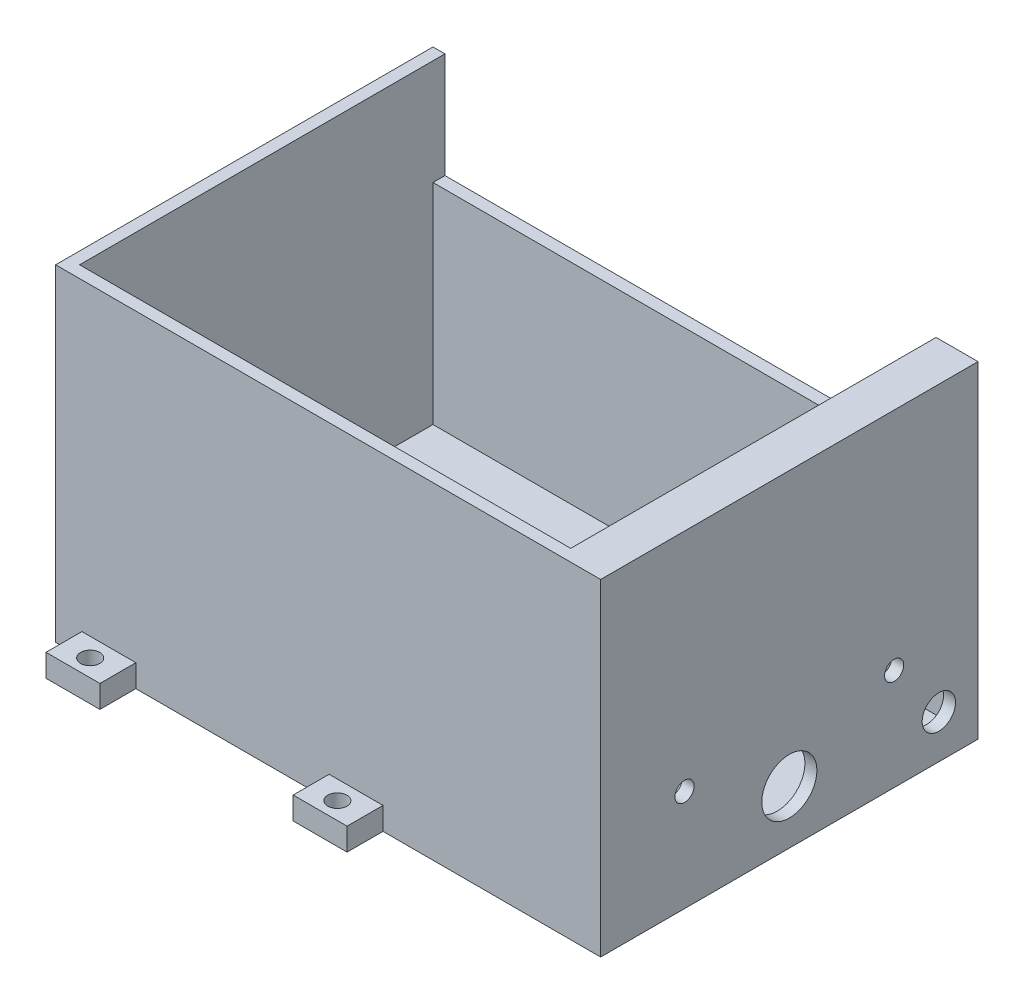
SolidWorks part; units mm, degrees
ref_plane "前视基准面" through (0, 0, 0) normal (0, 0, 1) x (1, 0, 0)
ref_plane "上视基准面" through (0, 0, 0) normal (0, 1, 0) x (1, 0, 0)
ref_plane "右视基准面" through (0, 0, 0) normal (1, 0, 0) x (0, 0, -1)
sketch "草图1" plane through (0, 0, 0) normal (0, 1, 0) x (1, 0, 0)
  line L1 (-43, 31.5) -> (43, 31.5)
  line L2 (-43, 31.5) -> (-43, -31.5)
  line L3 (-43, -31.5) -> (43, -31.5)
  line L4 (43, 31.5) -> (43, -31.5)
  point P4 (0, 31.5)
  point P7 (43, 0)
  dimension "D1" = 86
  dimension "D2" = 63
extrude "凸台-拉伸1" add sketch "草图1" along normal blind 2
sketch "草图2" plane through (0, 2, 0) normal (0, 1, 0) x (1, 0, 0)
  line L4 (-43, 31.5) -> (-43, -31.5)
  line L5 (-43, -31.5) -> (43, -31.5)
  line L6 (43, -31.5) -> (43, 31.5)
  line L7 (43, 31.5) -> (-43, 31.5)
  line L8 (-43, 31.5) -> (-43, -31.5)
  line L9 (-43, -31.5) -> (43, -31.5)
  line L10 (43, -31.5) -> (43, 31.5)
  line L11 (43, 31.5) -> (-43, 31.5)
  line L16 (-41, 29.5) -> (-41, -29.5)
  line L17 (-41, -29.5) -> (41, -29.5)
  line L18 (41, -29.5) -> (41, 29.5)
  line L19 (41, 29.5) -> (-41, 29.5)
  line L20 (-41, 29.5) -> (-41, -29.5)
  line L21 (-41, -29.5) -> (41, -29.5)
  line L22 (41, -29.5) -> (41, 29.5)
  line L23 (41, 29.5) -> (-41, 29.5)
  dimension "D1" = 0
  dimension "D2" = 2
extrude "凸台-拉伸3" add sketch "草图2" along normal blind 52.6
sketch "草图4" plane through (0, 0, -29.5) normal (0, 0, 1) x (1, 0, 0)
  line L0 (-41, 37) -> (41, 37)
  line L1 (-41, 54.6) -> (-41, 37)
  line L4 (-41, 2) -> (41, 2)
  line L5 (41, 2) -> (41, 54.6)
  line L6 (41, 54.6) -> (-41, 54.6)
  line L7 (-41, 54.6) -> (-41, 2)
  line L8 (-41, 2) -> (41, 2)
  line L9 (41, 2) -> (41, 54.6)
  line L10 (41, 54.6) -> (-41, 54.6)
  line L11 (-41, 54.6) -> (-41, 2)
  line M7 (41, 2) -> (41, 54.6)
  line M8 (41, 54.6) -> (-41, 54.6)
  line M9 (-41, 54.6) -> (-41, 2)
  dimension "D2" = 17.6
  dimension "D1" = 0
extrude "切除-拉伸1" cut sketch "草图4" against normal blind 52.6 contours L0 M9 M7 M8
sketch "草图5" plane through (43, 0, 0) normal (1, 0, 0) x (0, 0, -1)
  line L0 (0, 8.9545) -> (0, 16.9545)
  line L4 (-31.5, 0) -> (31.5, 0)
  line L5 (31.5, 0) -> (31.5, 54.6)
  line L6 (31.5, 54.6) -> (-31.5, 54.6)
  line L7 (-31.5, 54.6) -> (-31.5, 0)
  line L8 (-31.5, 0) -> (31.5, 0)
  line L9 (31.5, 0) -> (31.5, 54.6)
  line L10 (31.5, 54.6) -> (-31.5, 54.6)
  line L11 (-31.5, 54.6) -> (-31.5, 0)
  line L12 (-17.5, 16.9545) -> (17.5, 16.9545) construction
  line L16 (-29.5, 2) -> (29.5, 2)
  line L17 (29.5, 2) -> (29.5, 52.6)
  line L18 (29.5, 52.6) -> (-29.5, 52.6)
  line L19 (-29.5, 52.6) -> (-29.5, 2)
  line L20 (-29.5, 2) -> (29.5, 2)
  line L21 (29.5, 2) -> (29.5, 52.6)
  line L22 (29.5, 52.6) -> (-29.5, 52.6)
  line L23 (-29.5, 52.6) -> (-29.5, 2)
  circle A0 centre (-17.5, 16.9545) radius 1.6
  circle A1 centre (17.5, 16.9545) radius 1.6
  circle A2 centre (0, 8.9545) radius 4.6
  point P12 (0, 2)
  point P13 (0, 16.9545)
  point P16 (0, 0)
  point P18 (-2.5678, 32.2353)
  point P19 (0, 0)
  point P20 (0, 0)
  dimension "D3" = 3.2
  dimension "D4" = 3.2
  dimension "D6" = 9.2
  dimension "D5" = 35
  dimension "D7" = 8
  dimension "D1" = 0
  dimension "D2" = 2
extrude "切除-拉伸2" cut sketch "草图5" against normal up to surface (2 mm away) up to face at (41, 31.2, -10.5)
sketch "草图7" plane through (0, 2, 0) normal (0, 1, 0) x (1, 0, 0)
  line L0 (-38.17, -26.73) -> (-38.17, -29.5)
  line L1 (41, -26.73) -> (36.38, -26.73)
  line L4 (41, 29.5) -> (-41, 29.5)
  line L5 (-41, 29.5) -> (-41, -29.5)
  line L6 (-41, -29.5) -> (41, -29.5)
  line L7 (41, -29.5) -> (41, 29.5)
  line L8 (41, 29.5) -> (-41, 29.5)
  line L9 (-41, 29.5) -> (-41, -29.5)
  line L10 (-41, -29.5) -> (41, -29.5)
  line L11 (41, -29.5) -> (41, 29.5)
  circle A0 centre (-38.17, 6.16) radius 1.6
  circle A1 centre (36.38, 6.16) radius 1.6
  circle A2 centre (-38.17, -26.73) radius 1.6
  circle A3 centre (36.38, -26.73) radius 1.6
  dimension "D2" = 3.2
  dimension "D3" = 3.2
  dimension "D4" = 3.2
  dimension "D5" = 3.2
  dimension "D6" = 74.55
  dimension "D7" = 32.89
  dimension "D8" = 2.77
  dimension "D9" = 4.62
  dimension "D1" = 0
extrude "切除-拉伸6" cut sketch "草图7" against normal blind 2
sketch "草图8" plane through (0, 2, 0) normal (0, 1, 0) x (1, 0, 0)
  line L0 (-41, 29.5) -> (-41, -29.5) construction
  line L1 (-38.17, 6.16) -> (-38.17, -26.73)
  line L2 (-39, 1.715) -> (-39, -22.285)
  circle A0 centre (-39, 1.715) radius 1.6
  circle A1 centre (21, -22.285) radius 1.6
  circle A2 centre (-39, -22.285) radius 1.5161
  circle A3 centre (21, 1.715) radius 1.6
  circle A4 centre (-38.17, 6.16) radius 1.6 construction
  circle A5 centre (-38.17, -26.73) radius 1.6 construction
  circle A6 centre (-38.17, -26.73) radius 1.6
  circle A7 centre (-38.17, 6.16) radius 1.6
  point P8 (-39, -10.285)
  point P9 (-38.17, -10.285)
  dimension "D1" = 3.2
  dimension "D2" = 3.2
  dimension "D3" = 3.2
  dimension "D4" = 60
  dimension "D5" = 24
  dimension "D6" = 2
extrude "切除-拉伸7" cut sketch "草图8" against normal blind 2 contours A0 | A2 | A1 | A3
sketch "草图9" plane through (43, 0, 0) normal (1, 0, 0) x (0, 0, -1)
  line L4 (-31.5, 0) -> (31.5, 0)
  line L5 (31.5, 0) -> (31.5, 54.6)
  line L6 (31.5, 54.6) -> (-31.5, 54.6)
  line L7 (-31.5, 54.6) -> (-31.5, 0)
  line L8 (-31.5, 0) -> (31.5, 0)
  line L9 (31.5, 0) -> (31.5, 54.6)
  line L10 (31.5, 54.6) -> (-31.5, 54.6)
  line L11 (-31.5, 54.6) -> (-31.5, 0)
  dimension "D1" = 0
extrude "凸台-拉伸4" add sketch "草图9" along normal blind 5
sketch "草图10" plane through (48, 0, 0) normal (1, 0, 0) x (0, 0, -1)
  circle A0 centre (-17.5, 16.9545) radius 1.6 construction
  circle A1 centre (0, 8.9545) radius 4.6 construction
  circle A2 centre (17.5, 16.9545) radius 1.6 construction
  circle A3 centre (-17.5, 16.9545) radius 1.6
  circle A4 centre (0, 8.9545) radius 4.6
  circle A5 centre (17.5, 16.9545) radius 1.6
extrude "切除-拉伸8" cut sketch "草图10" against normal blind 5
sketch "草图11" plane through (41, 0, 0) normal (-1, 0, 0) x (0, 0, 1)
  line L1 (-31.5, 54.6) -> (29.5, 54.6)
  line L2 (-31.5, 54.6) -> (-31.5, 52.6)
  line L3 (-31.5, 52.6) -> (29.5, 52.6)
  line L4 (29.5, 54.6) -> (29.5, 52.6)
  line L6 (-29.5, 2) -> (29.5, 2)
  line L7 (29.5, 2) -> (29.5, 54.6)
  line L8 (29.5, 54.6) -> (-31.5, 54.6)
  line L9 (-31.5, 54.6) -> (-31.5, 37)
  line L10 (-31.5, 37) -> (-29.5, 37)
  line L11 (-29.5, 37) -> (-29.5, 2)
  line L12 (-29.5, 2) -> (29.5, 2)
  line L13 (29.5, 2) -> (29.5, 54.6)
  line L14 (29.5, 54.6) -> (-31.5, 54.6)
  line L15 (-31.5, 54.6) -> (-31.5, 37)
  line L16 (-31.5, 37) -> (-29.5, 37)
  line L17 (-29.5, 37) -> (-29.5, 2)
  circle M7 centre (-17.5, 16.9545) radius 1.6
  circle M8 centre (0, 8.9545) radius 4.6
  circle M9 centre (17.5, 16.9545) radius 1.6
  line M10 (-29.5, 2) -> (29.5, 2)
  line M11 (29.5, 2) -> (29.5, 54.6)
  line M13 (-31.5, 54.6) -> (-31.5, 37)
  line M14 (-31.5, 37) -> (-29.5, 37)
  line M15 (-29.5, 37) -> (-29.5, 2)
  dimension "D2" = 2
  dimension "D1" = 0
extrude "切除-拉伸9" cut sketch "草图11" against normal blind 5 contours L3 M13 M14 M15 M10 M11 M8 M9 M7
sketch "草图12" plane through (0, 0, -31.5) normal (0, 0, -1) x (-1, 0, 0)
  line L0 (-41, 52.6) -> (-41, 37)
  line L10 (-46, 52.6) -> (-41, 52.6)
  line L11 (-41, 52.6) -> (-41, 54.6)
  line L12 (-41, 54.6) -> (-48, 54.6)
  line L13 (-48, 54.6) -> (-48, 0)
  line L14 (-48, 0) -> (43, 0)
  line L15 (43, 0) -> (43, 54.6)
  line L16 (43, 54.6) -> (41, 54.6)
  line L17 (41, 54.6) -> (41, 37)
  line L18 (41, 37) -> (-46, 37)
  line L19 (-46, 37) -> (-46, 52.6)
  line L20 (-46, 52.6) -> (-41, 52.6)
  line L21 (-41, 52.6) -> (-41, 54.6)
  line L22 (-41, 54.6) -> (-48, 54.6)
  line L23 (-48, 54.6) -> (-48, 0)
  line L24 (-48, 0) -> (43, 0)
  line L25 (43, 0) -> (43, 54.6)
  line L26 (43, 54.6) -> (41, 54.6)
  line L27 (41, 54.6) -> (41, 37)
  line L28 (41, 37) -> (-46, 37)
  line L29 (-46, 37) -> (-46, 52.6)
  line M11 (-46, 52.6) -> (-41, 52.6)
  line M19 (41, 37) -> (-46, 37)
  line M20 (-46, 37) -> (-46, 52.6)
  dimension "D1" = 0
extrude "凸台-拉伸5" add sketch "草图12" against normal blind 2 contours L0 M11 M20 M19
sketch "草图13" plane through (48, 0, 0) normal (1, 0, 0) x (0, 0, -1)
  circle A0 centre (24.9631, 7.2089) radius 2.7875
extrude "切除-拉伸10" cut sketch "草图13" against normal blind 2
sketch "草图14" plane through (0, 0, -31.5) normal (0, 0, -1) x (-1, 0, 0)
  circle A0 centre (-28.0594, 7.3654) radius 3
  point P2 (0, 0)
  point P3 (-28.0594, 7.3654)
  dimension "D1" = 6
extrude "切除-拉伸11" cut sketch "草图14" against normal blind 2
sketch "草图16" plane through (0, 0, -31.5) normal (0, 0, -1) x (-1, 0, 0)
  line L0 (43, 0) -> (-27, 0)
  line L1 (-48, 0) -> (43, 0) construction
  line L3 (38.6107, 0) -> (29.6107, 0)
  line L4 (38.6107, 0) -> (38.6107, 3.7589)
  line L5 (38.6107, 3.7589) -> (29.6107, 3.7589)
  line L6 (29.6107, 0) -> (29.6107, 3.7589)
  line L8 (-2.6582, 3.76) -> (-11.6582, 3.76)
  line L9 (-2.6582, 3.76) -> (-2.6582, 0)
  line L10 (-2.6582, 0) -> (-11.6582, 0)
  line L11 (-11.6582, 3.76) -> (-11.6582, 0)
  dimension "D1" = 70
  dimension "D2" = 9
  dimension "D3" = 3.7589
  dimension "D4" = 9
  dimension "D5" = 3.76
extrude "凸台-拉伸6" add sketch "草图16" along normal blind 6 contours L6 L0 L4 L5 | L8 L11 L0 L9
sketch "草图17" plane through (0, 3.7589, 0) normal (0, 1, 0) x (1, 0, 0)
  line L0 (-38.6107, 37.5) -> (-29.6107, 37.5) construction
  line L1 (2.6582, 37.5) -> (11.6582, 37.5) construction
  circle A0 centre (-34.1107, 34.6252) radius 1.6
  circle A1 centre (7.1582, 34.6252) radius 1.6
  point P2 (0, 0)
  point P5 (-34.0255, 34.6252)
  point P8 (-34.1107, 37.5)
  point P9 (0, 0)
  point P12 (7.1582, 37.5)
  dimension "D1" = 3.2
  dimension "D2" = 3.2
extrude "切除-拉伸15" cut sketch "草图17" against normal through all both and the other way through all
sketch "草图18" plane through (0, 0, 0) normal (0, -1, 0) x (1, 0, 0)
  line L0 (48, 0) -> (-43, 0) construction
  line L1 (-38.6107, 31.5) -> (-38.6107, 37.5)
  line L2 (-38.6107, 37.5) -> (-29.6107, 37.5)
  line L3 (-29.6107, 37.5) -> (-29.6107, 31.5)
  line L4 (2.6582, 31.5) -> (2.6582, 37.5)
  line L5 (2.6582, 37.5) -> (11.6582, 37.5)
  line L6 (11.6582, 37.5) -> (11.6582, 31.5)
  line L12 (-43, 31.5) -> (-43, -31.5)
  line L13 (-43, -31.5) -> (-38.6107, -31.5)
  line L14 (-38.6107, -31.5) -> (-38.6107, -37.5)
  line L15 (-38.6107, -37.5) -> (-29.6107, -37.5)
  line L16 (-29.6107, -37.5) -> (-29.6107, -31.5)
  line L17 (-29.6107, -31.5) -> (2.6582, -31.5)
  line L18 (2.6582, -31.5) -> (2.6582, -37.5)
  line L19 (2.6582, -37.5) -> (11.6582, -37.5)
  line L20 (11.6582, -37.5) -> (11.6582, -31.5)
  line L21 (11.6582, -31.5) -> (48, -31.5)
  line L22 (48, -31.5) -> (48, 31.5)
  line L23 (48, 31.5) -> (-43, 31.5)
  line L24 (-43, 31.5) -> (-43, -31.5)
  line L25 (-43, -31.5) -> (-38.6107, -31.5)
  line L26 (-38.6107, -31.5) -> (-38.6107, -37.5)
  line L27 (-38.6107, -37.5) -> (-29.6107, -37.5)
  line L28 (-29.6107, -37.5) -> (-29.6107, -31.5)
  line L29 (-29.6107, -31.5) -> (2.6582, -31.5)
  line L30 (2.6582, -31.5) -> (2.6582, -37.5)
  line L31 (2.6582, -37.5) -> (11.6582, -37.5)
  line L32 (11.6582, -37.5) -> (11.6582, -31.5)
  line L33 (11.6582, -31.5) -> (48, -31.5)
  line L34 (48, -31.5) -> (48, 31.5)
  line L35 (48, 31.5) -> (-43, 31.5)
  circle A0 centre (7.1582, -34.6252) radius 1.6 construction
  circle A1 centre (7.1582, -34.6252) radius 1.6
  circle A2 centre (-34.1107, -34.6252) radius 1.6 construction
  circle A3 centre (-34.1107, -34.6252) radius 1.6
  circle A4 centre (-34.1107, 34.6252) radius 1.6
  circle A5 centre (7.1582, 34.6252) radius 1.6
  point P20 (-43, 0)
  point P21 (-29.6107, -34.5)
  point P22 (-38.6107, -34.5)
  point P25 (-38.6107, 34.5)
  point P29 (-29.6107, 34.5)
  line M33 (48, 31.5) -> (-43, 31.5)
  dimension "D1" = 0
extrude "凸台-拉伸7" add sketch "草图18" against normal blind 3.76 contours L6 L5 L4 A5 M33 | L3 L2 L1 A4 M33
